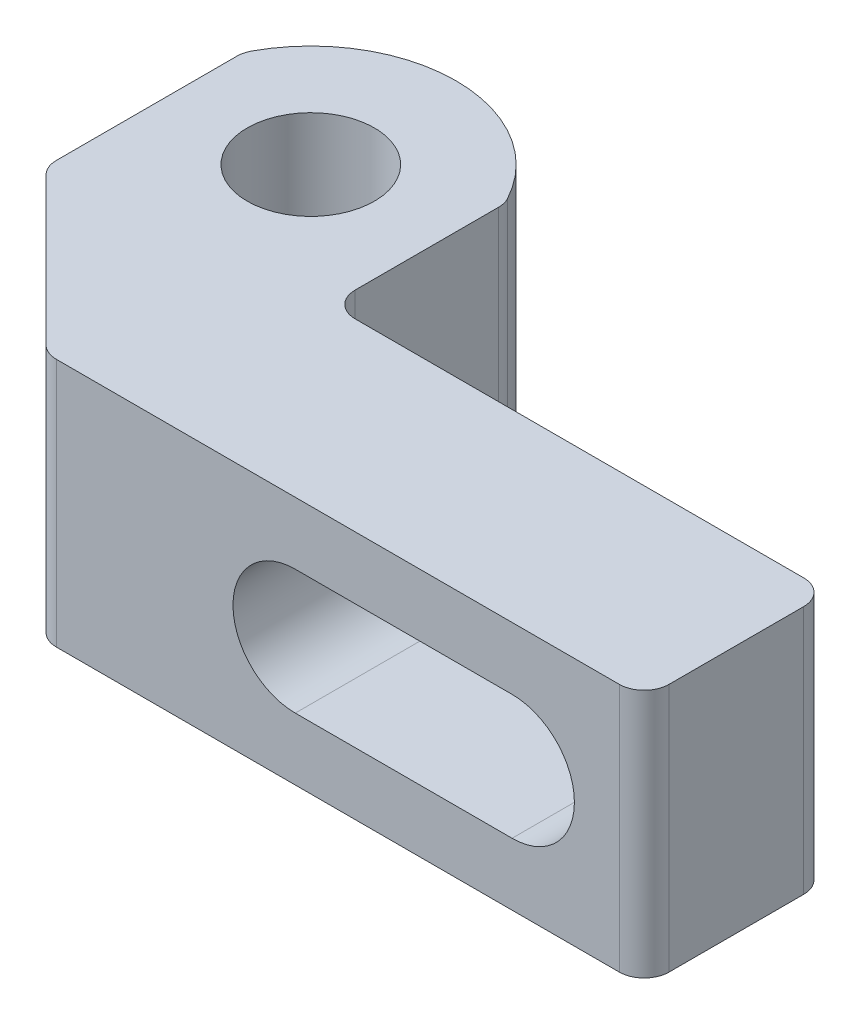
SolidWorks part; units mm, degrees
ref_plane "Front Plane" through (0, 0, 0) normal (0, 0, 1) x (1, 0, 0)
ref_plane "Top Plane" through (0, 0, 0) normal (0, 1, 0) x (1, 0, 0)
ref_plane "Right Plane" through (0, 0, 0) normal (1, 0, 0) x (0, 0, -1)
sketch "Sketch1" plane through (0, 0, 0) normal (0, 1, 0) x (1, 0, 0)
  line L0 (0, 0) -> (0, 7.4)
  line L1 (0, 7.4) -> (-20, 7.4)
  line L2 (-20, 7.4) -> (-20, 14.4)
  line L3 (0, 0) -> (-24, 0)
  line L4 (-24, 0) -> (-30.5, 6.5)
  line L5 (-30.5, 6.5) -> (-30.5, 14.4)
  line L6 (-30.5, 14.4) -> (-20, 14.4) construction
  arc A0 (-30.5, 14.4) -> (-20, 14.4) centre (-25.25, 11.8739) cw
  circle A1 centre (-25.25, 11.8739) radius 2.55
  dimension "D7" = 3.3
  dimension "D8" = 5.1
  dimension "D1" = 7.4
  dimension "D2" = 10.5
  dimension "D3" = 20
  dimension "D4" = 24
  dimension "D5" = 135
  dimension "D6" = 7
extrude "Boss-Extrude1" add sketch "Sketch1" along normal blind 10
sketch "Sketch3" plane through (0, 0, -7.4) normal (0, 0, -1) x (-1, 0, 0)
  line L0 (20, 5) -> (0, 5) construction
  line L1 (20, 10) -> (20, 0) construction
  line L2 (0, 10) -> (0, 0) construction
  line L3 (14, 5) -> (5.3, 5) construction
  line L4 (14, 2.5) -> (5.3, 2.5)
  line L5 (14, 7.5) -> (5.3, 7.5)
  arc A0 (14, 2.5) -> (14, 7.5) centre (14, 5) ccw
  arc A1 (5.3, 7.5) -> (5.3, 2.5) centre (5.3, 5) ccw
  point P8 (9.65, 5)
  dimension "D1" = 5
  dimension "D2" = 2.8
  dimension "D3" = 3.5
extrude "Cut-Extrude1" cut sketch "Sketch3" against normal through all
fillet "Fillet2" radius 1 7 edges at (-24, 5, 0) (-30.5, 5, -6.5) (-30.5, 5, -14.4) (-20, 5, -14.4) (-20, 5, -7.4) (0, 5, -7.4) (0, 5, 0)
